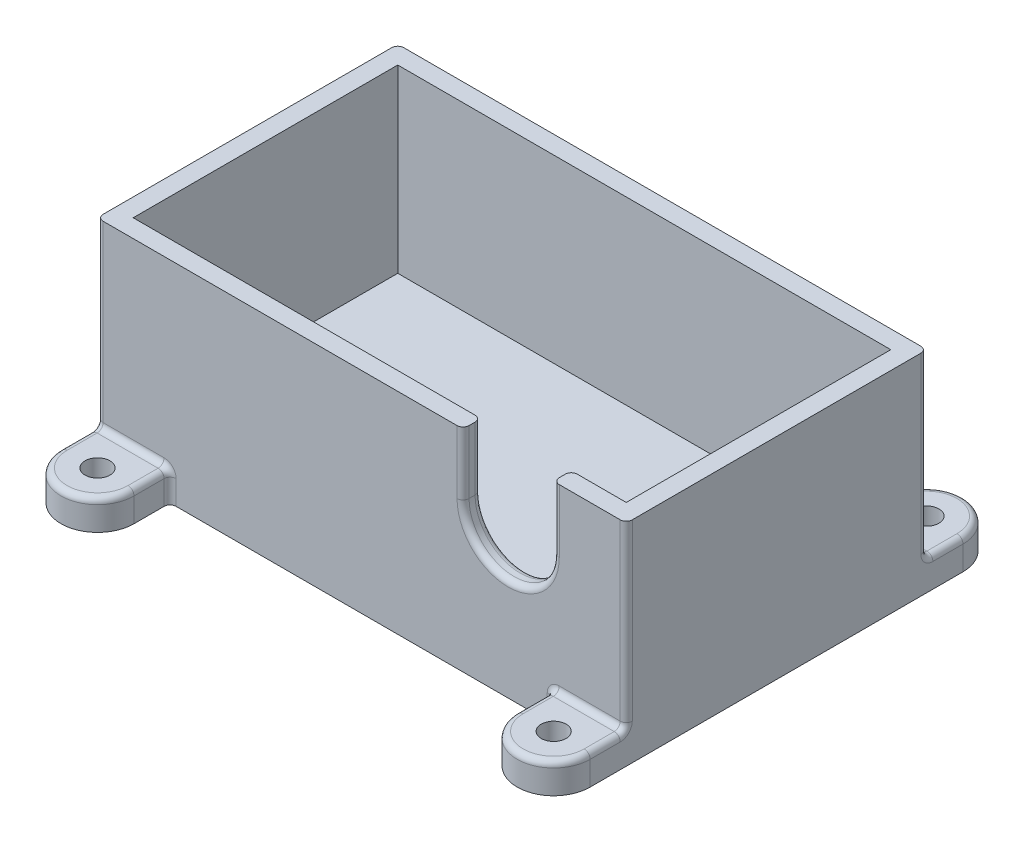
SolidWorks part; units mm, degrees
material "ABS"
ref_plane "Front Plane" through (0, 0, 0) normal (0, 0, 1) x (1, 0, 0)
ref_plane "Top Plane" through (0, 0, 0) normal (0, 1, 0) x (1, 0, 0)
ref_plane "Right Plane" through (0, 0, 0) normal (1, 0, 0) x (0, 0, -1)
sketch "Sketch2" plane through (0, 0, 0) normal (0, 1, 0) x (1, 0, 0)
  line L0 (-44, 25) -> (44, 25) construction
  line L1 (-44, 50) -> (44, 50)
  line L2 (-44, 50) -> (-44, 0)
  line L3 (-44, 0) -> (44, 0)
  line L4 (0, 50) -> (0, 0)
  line L5 (-44, 0) -> (-31.86, 0)
  line L6 (-44, 0) -> (-44, -6)
  line L8 (-31.86, 0) -> (-31.86, -6)
  line L9 (-44, 50) -> (-44, 56)
  line L10 (-31.86, 50) -> (-31.86, 56)
  line L11 (31.86, 50) -> (31.86, 56)
  line L12 (44, 50) -> (44, 56)
  line L13 (31.86, 0) -> (31.86, -6)
  line L14 (44, 0) -> (44, -6)
  line L15 (44, 0) -> (31.86, 0)
  line L16 (44, 50) -> (44, 0)
  arc A0 (-44, -6) -> (-31.86, -6) centre (-37.93, -6) ccw
  circle A1 centre (-37.93, -6) radius 2.07
  arc A2 (-44, 56) -> (-31.86, 56) centre (-37.93, 56) cw
  circle A3 centre (-37.93, 56) radius 2.07
  circle A4 centre (37.93, 56) radius 2.07
  arc A5 (44, 56) -> (31.86, 56) centre (37.93, 56) ccw
  circle A6 centre (37.93, -6) radius 2.07
  arc A7 (44, -6) -> (31.86, -6) centre (37.93, -6) cw
  point P18 (0, 25)
  dimension "D1" = 4.14
  dimension "D2" = 4
  dimension "D5" = 6
  dimension "D3" = 50
  dimension "D4" = 44
extrude "Boss-Extrude1" add sketch "Sketch2" along normal blind 5 contours L6 A0 L8 L3 A1 | L0 L2 L3 L4 | L2 L0 L4 L1 | A2 L9 L1 L10 A3 | A7 L14 L3 L13 A6 | L12 A5 L11 L1 A4 | L4 L0 L16 L1 | L0 L4 L3 L16
sketch "Sketch3" plane through (0, 5, 0) normal (0, 1, 0) x (1, 0, 0)
  line L0 (-31.86, 50) -> (-44, 50) construction
  line L1 (-44, 56) -> (-44, -6) construction
  line L2 (44, 56) -> (44, -6) construction
  line L3 (-44, 50) -> (44, 50)
  line L4 (-44, 50) -> (-44, 0)
  line L5 (-44, 0) -> (44, 0)
  line L6 (44, 50) -> (44, 0)
  line L8 (-41, 47) -> (41, 47)
  line L9 (-41, 47) -> (-41, 3)
  line L10 (-41, 3) -> (41, 3)
  line L11 (41, 47) -> (41, 3)
  point P14 (-44, 25)
  dimension "D1" = 3
  dimension "D2" = 3
  dimension "D3" = 3
  dimension "D4" = 3
extrude "Boss-Extrude2" add sketch "Sketch3" along normal blind 30
sketch "Sketch4" plane through (0, 0, 0) normal (0, 0, 1) x (1, 0, 0)
  line L0 (31.86, 5) -> (31.86, 35) construction
  line L1 (-44, 35) -> (44, 35) construction
  line L2 (24.36, 24.4948) -> (24.36, 38.2604) construction
  line L3 (16.86, 24.4948) -> (16.86, 38.2604)
  line L4 (31.86, 24.4948) -> (31.86, 38.2604)
  arc A0 (16.86, 24.4948) -> (31.86, 24.4948) centre (24.36, 24.4948) ccw
  arc A1 (31.86, 38.2604) -> (16.86, 38.2604) centre (24.36, 38.2604) ccw
  point P7 (24.36, 31.3776)
  point P12 (31.86, 17.9602)
  point P13 (19.0517, 24.4948)
  point P14 (25.8686, 38.2604)
  dimension "D1" = 15
extrude "Cut-Extrude1" cut sketch "Sketch4" against normal blind 30
fillet "Fillet1" radius 1 30 edges at (44, 20, 0) (31.86, 2.5, 0) (-31.86, 2.5, 0) (-44, 20, -50) (-31.86, 2.5, -50) (31.86, 2.5, -50) (44, 20, -50) (31.86, 29.7474, -3) (16.86, 29.7474, -3) (16.86, 29.7474, 0) (31.86, 29.7474, 0) (44, 5, 3) (37.93, 5, 12.07) (31.86, 5, 3) (37.93, 5, 0) (-31.86, 5, 3) (-37.93, 5, 12.07) (-44, 5, 3) (-37.93, 5, 0) (-44, 5, -53) (-37.93, 5, -62.07) (-31.86, 5, -53) (-37.93, 5, -50) (31.86, 5, -53) (37.93, 5, -62.07) (44, 5, -53) (37.93, 5, -50) (24.36, 16.9948, -3) (24.36, 16.9948, 0) (-44, 20, 0)
